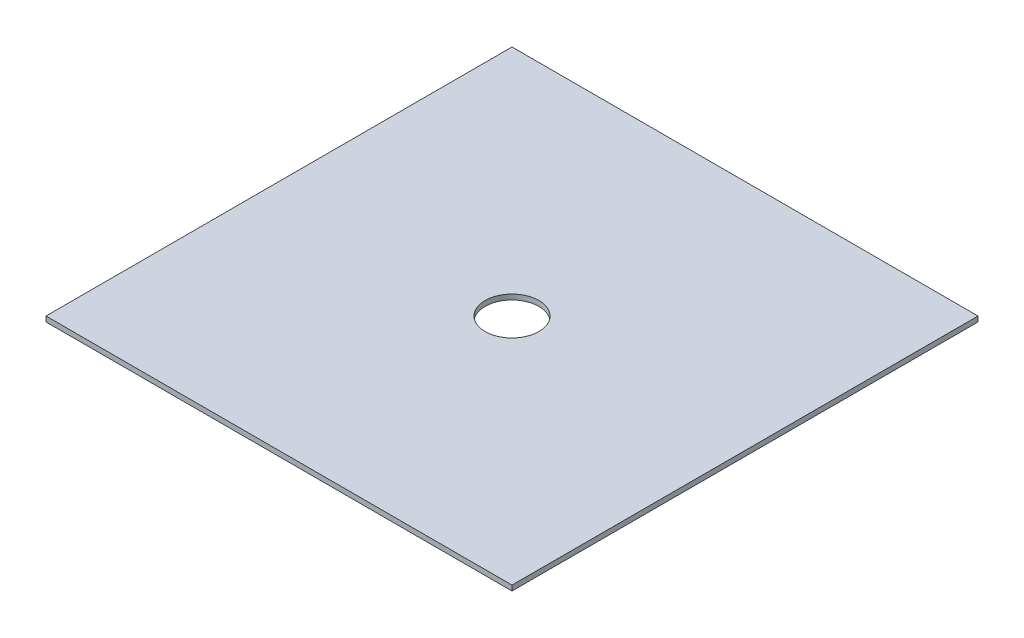
SolidWorks part; units mm, degrees
ref_plane "Front Plane" through (0, 0, 0) normal (0, 0, 1) x (1, 0, 0)
ref_plane "Top Plane" through (0, 0, 0) normal (0, 1, 0) x (1, 0, 0)
ref_plane "Right Plane" through (0, 0, 0) normal (1, 0, 0) x (0, 0, -1)
sketch "Sketch1" plane through (0, 0, 0) normal (0, 1, 0) x (1, 0, 0)
  line L0 (0, 285.75) -> (0, -285.75) construction
  line L1 (-285.75, 285.75) -> (285.75, 285.75)
  line L2 (-285.75, 285.75) -> (-285.75, -285.75)
  line L3 (-285.75, -285.75) -> (285.75, -285.75)
  line L4 (285.75, 285.75) -> (285.75, -285.75)
  line L5 (-285.75, 0) -> (285.75, 0) construction
  circle A0 centre (0, 0) radius 33.02
  point P6 (0, 0)
  dimension "D3" = 66.04
  dimension "D1" = 571.5
  dimension "D2" = 571.5
extrude "Boss-Extrude1" add sketch "Sketch1" along normal blind 6.35
